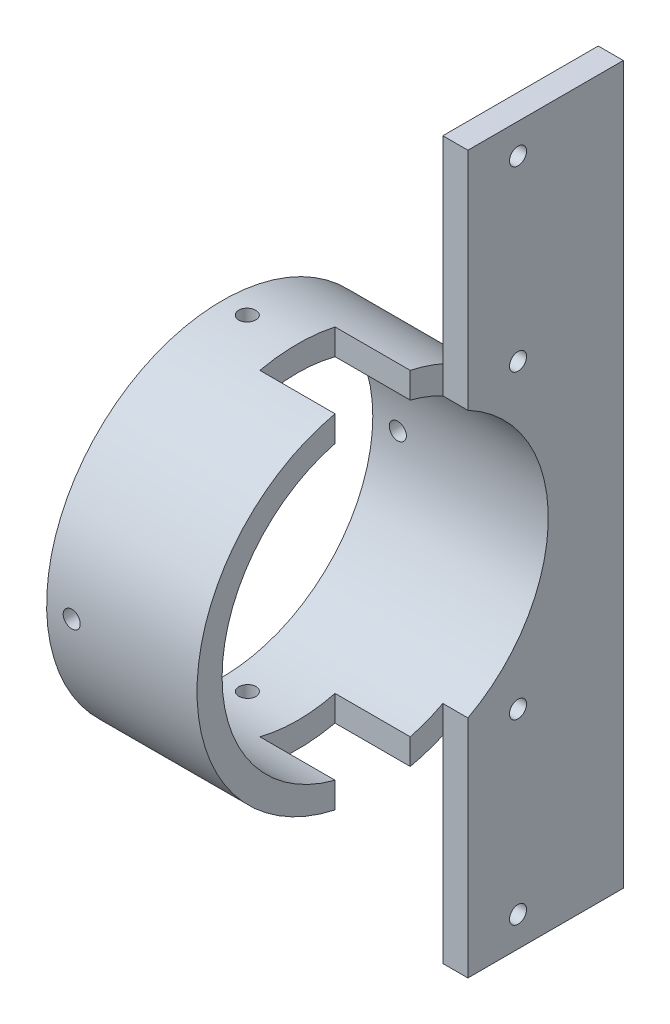
SolidWorks part; units mm, degrees
ref_plane "Front Plane" through (0, 0, 0) normal (0, 0, 1) x (1, 0, 0)
ref_plane "Top Plane" through (0, 0, 0) normal (0, 1, 0) x (1, 0, 0)
ref_plane "Right Plane" through (0, 0, 0) normal (1, 0, 0) x (0, 0, -1)
sketch "Sketch1" plane through (0, 0, 0) normal (1, 0, 0) x (0, 0, -1)
  circle A0 centre (0, 0) radius 30.0312
  circle A1 centre (0, 0) radius 35.0312
  dimension "D1" = 60.0625
  dimension "D2" = 5
extrude "Boss-Extrude1" add sketch "Sketch1" along normal blind 30
ref_plane "Plane1" through (0, 35.0312, 0) normal (0, 1, 0) x (1, 0, 0)
sketch "Sketch4" plane through (0, 35.0312, 0) normal (0, 1, 0) x (1, 0, 0)
  point P0 (5, 0)
  dimension "D1" = 5
hole_wizard "M3 Clearance Hole2" positions "Sketch4" profile "Sketch5" hole size "M3" standard "ANSI Metric" end condition through all
sketch "Sketch5" plane through (5, 35.0312, 0) normal (1, 0, 0) x (0, 0, 1)
  line L0 (0, 0) -> (0, 70.0625)
  line L1 (0, 70.0625) -> (1.7, 70.0625)
  line L2 (1.7, 70.0625) -> (1.7, 0)
  line L5 (1.7, 0) -> (0, 0)
  line L11 (0, -6.35) -> (0, 107.95) construction
  dimension "Thru Hole Dia." = 3.4
  dimension "Thru Hole Depth" = 70.0625
ref_plane "Plane2" through (0, 0, 35.0312) normal (0, 0, 1) x (1, 0, 0)
sketch "Sketch6" plane through (0, 0, 35.0312) normal (0, 0, 1) x (1, 0, 0)
  point P0 (5, 0)
  dimension "D1" = 5
hole_wizard "M3 Clearance Hole3" positions "Sketch6" profile "Sketch7" hole size "M3" standard "ANSI Metric" end condition through all
sketch "Sketch7" plane through (5, 0, 35.0312) normal (1, 0, 0) x (0, -1, 0)
  line L0 (0, 0) -> (0, 70.0625)
  line L1 (0, 70.0625) -> (1.7, 70.0625)
  line L2 (1.7, 70.0625) -> (1.7, 0)
  line L5 (1.7, 0) -> (0, 0)
  line L11 (0, -6.35) -> (0, 107.95) construction
  dimension "Thru Hole Dia." = 3.4
  dimension "Thru Hole Depth" = 70.0625
sketch "Sketch9" plane through (30, 0, 0) normal (1, 0, 0) x (0, 0, -1)
  line L0 (0, 0) -> (-14.9677, 0) construction
  line L1 (14, 71.5) -> (45, 71.5)
  line L2 (14, 71.5) -> (14, 26.5683)
  line L3 (14, -71.5) -> (45, -71.5)
  line L4 (45, 71.5) -> (45, -71.5)
  line L5 (-5, 74) -> (5, 74) construction
  line L6 (-5, 74) -> (-5, 19) construction
  line L7 (-5, 19) -> (5, 19) construction
  line L8 (5, 74) -> (5, 19) construction
  line L9 (5, -74) -> (5, -19) construction
  line L10 (-5, -19) -> (5, -19) construction
  line L11 (-5, -74) -> (-5, -19) construction
  line L12 (-5, -74) -> (5, -74) construction
  line L14 (14, -26.5683) -> (14, -71.5)
  line L15 (-4, 46.5) -> (14, 46.5) construction
  circle A0 centre (0, 0) radius 30.0312 construction
  arc A1 (14, -26.5683) -> (14, 26.5683) centre (0, 0) ccw
  point P11 (5, 46.5)
  point P17 (5, -46.5)
  point P22 (0, 74)
  point P25 (45, 0)
  dimension "D1" = 55
  dimension "D2" = 38
  dimension "D3" = 10
  dimension "D4" = 18
  dimension "D7" = 1
  dimension "D8" = 25
  dimension "D9" = 45
extrude "Boss-Extrude2" add sketch "Sketch9" along normal blind 5
sketch "Sketch11" plane through (35, 0, 0) normal (1, 0, 0) x (0, 0, -1)
  line L1 (1, 47.3937) -> (10, 47.3937)
  line L2 (1, 47.3937) -> (1, 39.1813)
  line L3 (1, 39.1813) -> (10, 39.1813)
  line L4 (10, 47.3937) -> (10, 39.1813)
  line L5 (10, 33.7924) -> (39, 33.7924)
  line L6 (10, 33.7924) -> (10, 51.1979)
  line L7 (10, 51.1979) -> (39, 51.1979)
  line L8 (39, 33.7924) -> (39, 51.1979)
  line L9 (34, 54.1979) -> (14, 54.1979)
  line L10 (34, 54.1979) -> (34, 31.3507)
  line L11 (34, 31.3507) -> (14, 31.3507)
  line L12 (14, 54.1979) -> (14, 31.3507)
  point P21 (39, 59.1979)
  dimension "D1" = 1
  dimension "D2" = 9
  dimension "D3" = 38
  dimension "D4" = 20
  dimension "D5" = 5
  dimension "D6" = 3
  dimension "D7" = 5
  dimension "D8" = 5
sketch "Sketch12" plane through (35, 0, 0) normal (1, 0, 0) x (0, 0, -1)
  line L2 (0, 0) -> (12.8828, 0) construction
  circle A0 centre (24, 65.5) radius 1.7 construction
  point P1 (24, 30.0342)
  point P14 (24, 65.5)
  point P24 (24, -65.5)
  point P25 (24, -30.0342)
  point P26 (24, 30.5)
  point P27 (24, 30.0342)
  point P29 (24, 65.5)
  point P31 (0, 0)
hole_wizard "M3 Clearance Hole4" positions "Sketch12" profile "Sketch13" hole size "M3" standard "ANSI Metric" end condition through all
sketch "Sketch13" plane through (35, 30.0342, -24) normal (0, 1, 0) x (0, 0, -1)
  line L0 (0, 0) -> (0, 35)
  line L1 (0, 35) -> (1.7, 35)
  line L2 (1.7, 35) -> (1.7, 0)
  line L5 (1.7, 0) -> (0, 0)
  line L11 (0, -6.35) -> (0, 107.95) construction
  dimension "Thru Hole Dia." = 3.4
  dimension "Thru Hole Depth" = 35
sketch "Sketch14" plane through (30, 0, 0) normal (1, 0, 0) x (0, 0, -1)
  line L1 (-7.5, 77.0088) -> (7.5, 77.0088)
  line L2 (-7.5, 77.0088) -> (-7.5, -46.9193)
  line L3 (-7.5, -46.9193) -> (7.5, -46.9193)
  line L4 (7.5, 77.0088) -> (7.5, -46.9193)
  point P4 (0, 77.0088)
  dimension "D1" = 15
  dimension "D2" = 46.9193
  dimension "D3" = 123.9281
extrude "Cut-Extrude1" cut sketch "Sketch14" against normal blind 15
